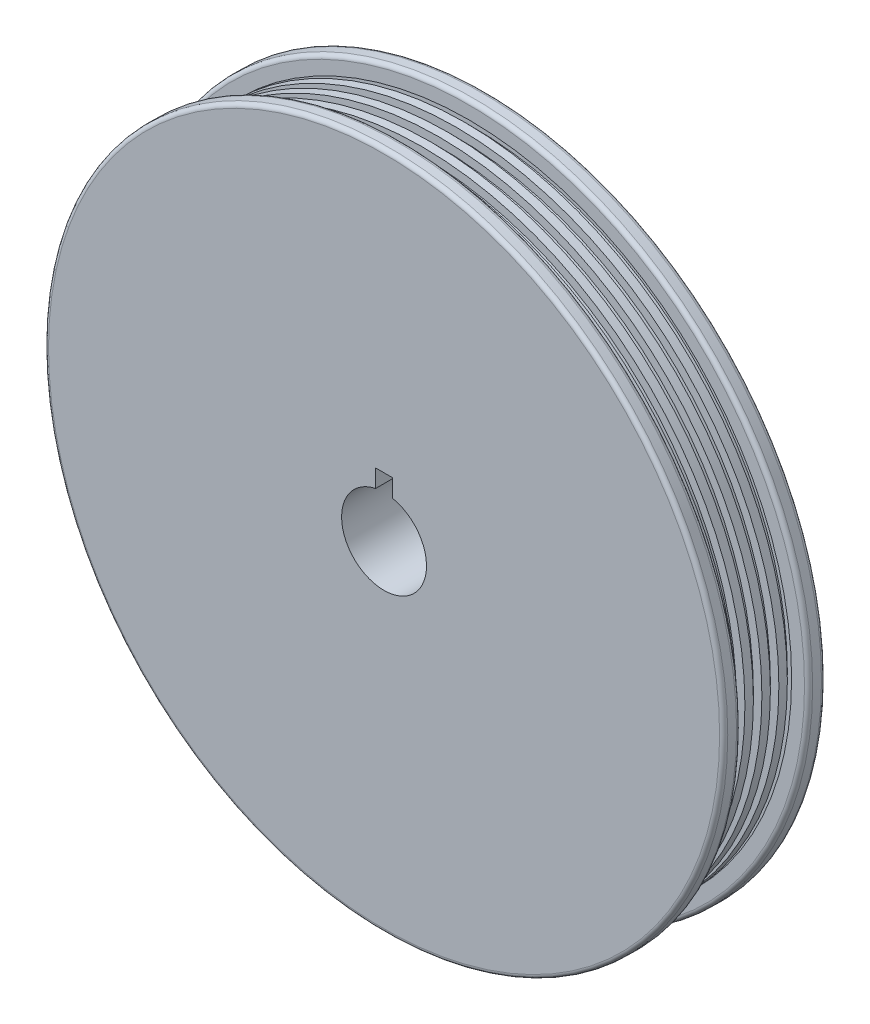
SolidWorks part; units mm, degrees
ref_plane "Front Plane" through (0, 0, 0) normal (0, 0, 1) x (1, 0, 0)
ref_plane "Top Plane" through (0, 0, 0) normal (0, 1, 0) x (1, 0, 0)
ref_plane "Right Plane" through (0, 0, 0) normal (1, 0, 0) x (0, 0, -1)
sketch "Sketch1" plane through (0, 0, 0) normal (0, 0, 1) x (1, 0, 0)
  circle A0 centre (0, 0) radius 127
  dimension "D1" = 254
extrude "Boss-Extrude1" add sketch "Sketch1" along normal mid plane 38.1
sketch "Sketch2" plane through (0, 0, 0) normal (0, 0, 1) x (1, 0, 0)
  circle A0 centre (0, 0) radius 127
  circle A1 centre (0, 0) radius 120.65
  dimension "D1" = 6.35
extrude "Cut-Extrude1" cut sketch "Sketch2" against normal mid plane 25.4
fillet "Fillet1" radius 1.524 4 edges at (127, 0, -19.05) (127, 0, 19.05) (127, 0, 12.7) (127, 0, -12.7)
sketch "Sketch3" plane through (0, 0, 0) normal (0, 0, 1) x (1, 0, 0)
  circle A0 centre (0, 0) radius 120.65
  circle A1 centre (0, 0) radius 127 construction
  circle A2 centre (0, 0) radius 117.475
  dimension "D1" = 6.35
  dimension "D2" = 3.175
extrude "Cut-Extrude2" cut sketch "Sketch3" against normal mid plane 3.175
pattern_linear "LPattern1" count 3 spacing 6.35 along (0, 0, -1) count 3 spacing 6.35 along (0, 0, 1) of "Cut-Extrude2"
sketch "Sketch4" plane through (0, 0, 19.05) normal (0, 0, 1) x (1, 0, 0)
  line L1 (-3.175, 22.225) -> (3.175, 22.225)
  line L2 (-3.175, 22.225) -> (-3.175, 15.5543)
  line L3 (-3.175, 9.525) -> (3.175, 9.525) construction
  line L4 (3.175, 22.225) -> (3.175, 15.5543)
  line L5 (-3.175, 22.225) -> (3.175, 9.525) construction
  line L6 (-3.175, 9.525) -> (3.175, 22.225) construction
  arc A0 (-3.175, 15.5543) -> (3.175, 15.5543) centre (0, 0) ccw
  point P3 (0, 15.875)
  dimension "D1" = 31.75
  dimension "D2" = 6.35
  dimension "D3" = 12.7
extrude "Cut-Extrude3" cut sketch "Sketch4" against normal blind 101.6
